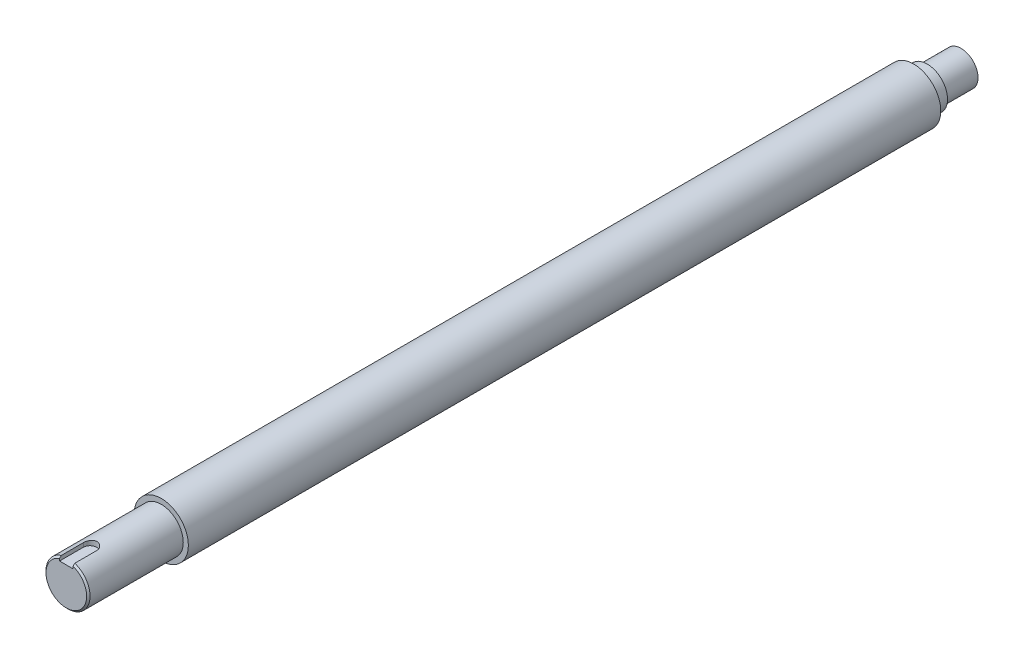
SolidWorks part; units mm, degrees
ref_plane "Front Plane" through (0, 0, 0) normal (0, 0, 1) x (1, 0, 0)
ref_plane "Top Plane" through (0, 0, 0) normal (0, 1, 0) x (1, 0, 0)
ref_plane "Right Plane" through (0, 0, 0) normal (1, 0, 0) x (0, 0, -1)
ref_plane "Plane1" through (0, 3.5, 0) normal (0, 1, 0) x (1, 0, 0)
sketch "Sketch1" plane through (0, 0, 0) normal (0, 0, 1) x (1, 0, 0)
  circle A0 centre (0, 0) radius 4
  dimension "D1" = 8
extrude "Boss-Extrude1" add sketch "Sketch1" along normal mid plane 132
sketch "Sketch2" plane through (0, 0, 66) normal (0, 0, 1) x (1, 0, 0)
  circle A0 centre (0, 0) radius 3.25
  circle A1 centre (0, 0) radius 4
  dimension "D1" = 6.5
extrude "Cut-Extrude1" cut sketch "Sketch2" against normal blind 14
sketch "Sketch3" plane through (0, 3.5, 0) normal (0, 1, 0) x (1, 0, 0)
  line L0 (0, -62.5) -> (0, -66) construction
  line L1 (-3.25, -66) -> (3.25, -66) construction
  line L2 (1, -62.5) -> (1, -66)
  line L3 (-1, -62.5) -> (-1, -66)
  arc A0 (1, -62.5) -> (-1, -62.5) centre (0, -62.5) ccw
  arc A1 (-1, -66) -> (1, -66) centre (0, -66) ccw
  point P4 (0, -64.25)
  dimension "D1" = 2
  dimension "D2" = 3.5
extrude "Cut-Extrude2" cut sketch "Sketch3" against normal blind 1
chamfer "Chamfer1" distance 0.25 angle 45 1 edges at (0, -3.25, 66)
sketch "Sketch5" plane through (0, 0, -66) normal (0, 0, -1) x (-1, 0, 0)
  circle A0 centre (0, 0) radius 4
  circle A1 centre (0, 0) radius 3
  dimension "D1" = 8
  dimension "D2" = 6
extrude "Cut-Extrude3" cut sketch "Sketch5" against normal blind 7
sketch "Sketch7" plane through (0, 0, -66) normal (0, 0, -1) x (-1, 0, 0)
  circle A0 centre (0, 0) radius 2.5
  circle A1 centre (0, 0) radius 3.566
  dimension "D1" = 5
extrude "Cut-Extrude4" cut sketch "Sketch7" against normal blind 5
sketch "Sketch8" plane through (0, 0, -66) normal (0, 0, -1) x (-1, 0, 0)
  line L0 (55, 3.5) -> (-55, 3.5) construction
  line L1 (0.75, -1.299) -> (1.5, 0)
  line L2 (1.5, 0) -> (0.75, 1.299)
  line L3 (0.75, 1.299) -> (-0.75, 1.299)
  line L4 (-0.75, 1.299) -> (-1.5, 0)
  line L5 (-1.5, 0) -> (-0.75, -1.299)
  line L6 (-0.75, -1.299) -> (0.75, -1.299)
  circle A0 centre (0, 0) radius 1.299 construction
  dimension "D1" = 1.5
extrude "Cut-Extrude5" cut sketch "Sketch8" against normal blind 5
sketch "Sketch10" plane through (0, 0, 0) normal (1, 0, 0) x (0, 0, -1)
  circle A0 centre (0, 0) radius 32.4955
